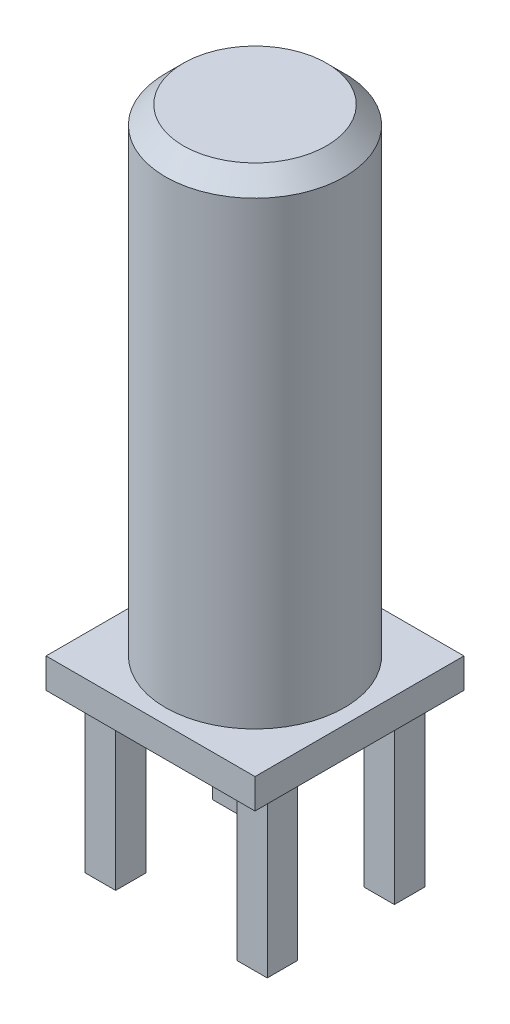
SolidWorks part; units mm, degrees
ref_plane "Front Plane" through (0, 0, 0) normal (0, 0, 1) x (1, 0, 0)
ref_plane "Top Plane" through (0, 0, 0) normal (0, 1, 0) x (1, 0, 0)
ref_plane "Right Plane" through (0, 0, 0) normal (1, 0, 0) x (0, 0, -1)
sketch "Sketch1" plane through (0, 0, 0) normal (0, 1, 0) x (1, 0, 0)
  line L1 (-3.5, 3.5) -> (3.5, 3.5)
  line L2 (-3.5, 3.5) -> (-3.5, -3.5)
  line L3 (-3.5, -3.5) -> (3.5, -3.5)
  line L4 (3.5, 3.5) -> (3.5, -3.5)
  line L5 (-3.5, 3.5) -> (3.5, -3.5) construction
  line L6 (-3.5, -3.5) -> (3.5, 3.5) construction
  point P0 (0, 0)
  dimension "D1" = 7
extrude "Boss-Extrude1" add sketch "Sketch1" along normal blind 1
sketch "Sketch2" plane through (0, 0, 0) normal (0, -1, 0) x (1, 0, 0)
  line L0 (-2.03, 1.6195) -> (2.03, -1.6195) construction
  line L1 (-3.05, 2.6395) -> (-2.03, 2.6395)
  line L2 (-3.05, 2.6395) -> (-3.05, 1.6195)
  line L3 (-3.05, 1.6195) -> (-2.03, 1.6195)
  line L4 (-2.03, 2.6395) -> (-2.03, 1.6195)
  line L5 (-3.05, -1.6195) -> (-2.03, -1.6195)
  line L6 (-3.05, -1.6195) -> (-3.05, -2.6395)
  line L7 (-3.05, -2.6395) -> (-2.03, -2.6395)
  line L8 (-2.03, -1.6195) -> (-2.03, -2.6395)
  line L9 (2.03, 2.6395) -> (3.05, 2.6395)
  line L10 (2.03, 2.6395) -> (2.03, 1.6195)
  line L11 (2.03, 1.6195) -> (3.05, 1.6195)
  line L12 (3.05, 2.6395) -> (3.05, 1.6195)
  line L13 (2.03, -1.6195) -> (3.05, -1.6195)
  line L14 (2.03, -1.6195) -> (2.03, -2.6395)
  line L15 (2.03, -2.6395) -> (3.05, -2.6395)
  line L16 (3.05, -1.6195) -> (3.05, -2.6395)
  dimension "D1" = 4.06
  dimension "D2" = 6.1
extrude "Boss-Extrude2" add sketch "Sketch2" along normal blind 5.5
sketch "Sketch4" plane through (0, 1, 0) normal (0, 1, 0) x (1, 0, 0)
  circle A0 centre (0, 0) radius 3
  dimension "D1" = 6
extrude "Boss-Extrude3" add sketch "Sketch4" along normal blind 16
chamfer "Chamfer1" distance 0.6 angle 45 1 edges at (0, 17, 3)
